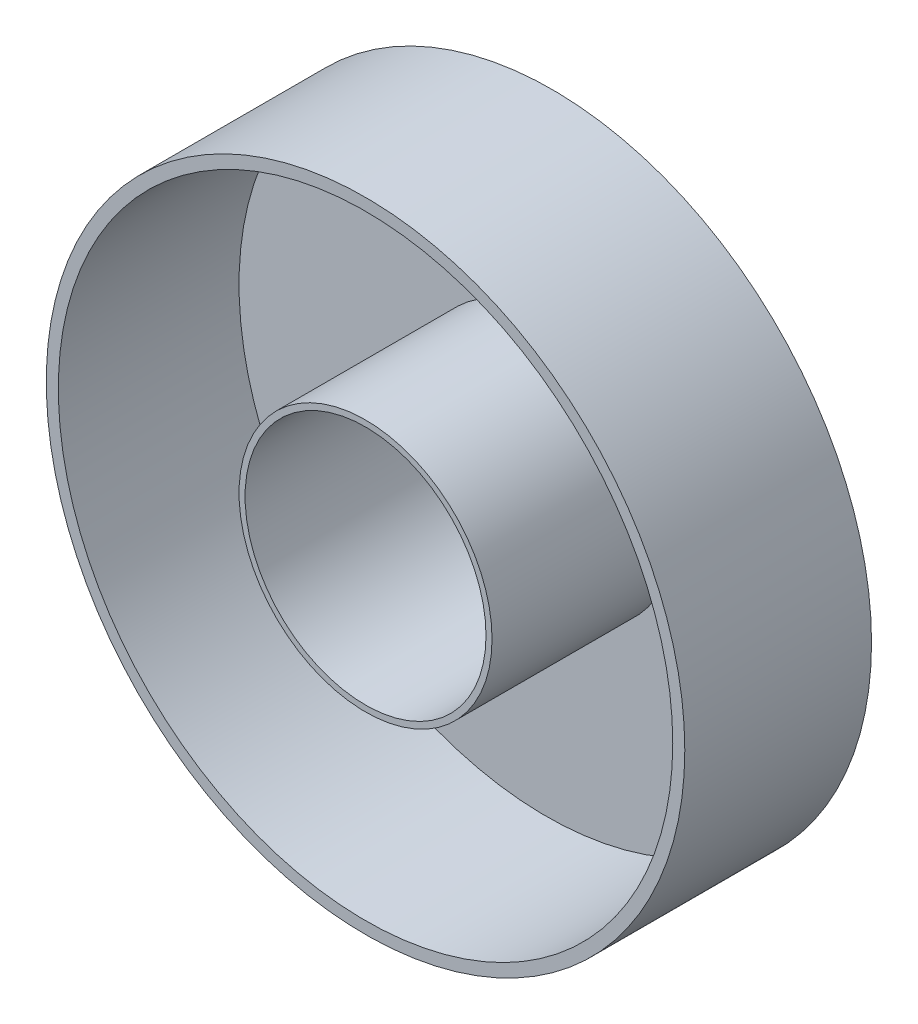
SolidWorks part; units mm, degrees
ref_plane "Front Plane" through (0, 0, 0) normal (0, 0, 1) x (1, 0, 0)
ref_plane "Top Plane" through (0, 0, 0) normal (0, 1, 0) x (1, 0, 0)
ref_plane "Right Plane" through (0, 0, 0) normal (1, 0, 0) x (0, 0, -1)
sketch "Sketch1" plane through (0, 0, 0) normal (0, 0, 1) x (1, 0, 0)
  circle A0 centre (0, 0) radius 26.5
  circle A1 centre (0, 0) radius 10.5
  circle A2 centre (0, 0) radius 25.5
  circle A3 centre (0, 0) radius 10
  dimension "D1" = 53
  dimension "D2" = 21
extrude "Boss-Extrude2" add sketch "Sketch1" along normal blind 0.5 contours A0 A2 | A1 A3
sketch "Sketch2" plane through (0, 0, 0.5) normal (0, 0, 1) x (1, 0, 0)
  circle A1 centre (0, 0) radius 10
  circle A2 centre (0, 0) radius 10
  circle A3 centre (0, 0) radius 25.5
  circle A4 centre (0, 0) radius 25.5
  circle A5 centre (0, 0) radius 10.5
  circle A6 centre (0, 0) radius 10.5
  circle A7 centre (0, 0) radius 26.5
  circle A8 centre (0, 0) radius 26.5
  circle M5 centre (0, 0) radius 26.5
  circle M6 centre (0, 0) radius 10.5
  dimension "D1" = 0
  dimension "D2" = 0
  dimension "D3" = 0
  dimension "D4" = 0
extrude "Boss-Extrude3" add sketch "Sketch2" along normal blind 15 contours A4 M5 | A2 M6 | A6
